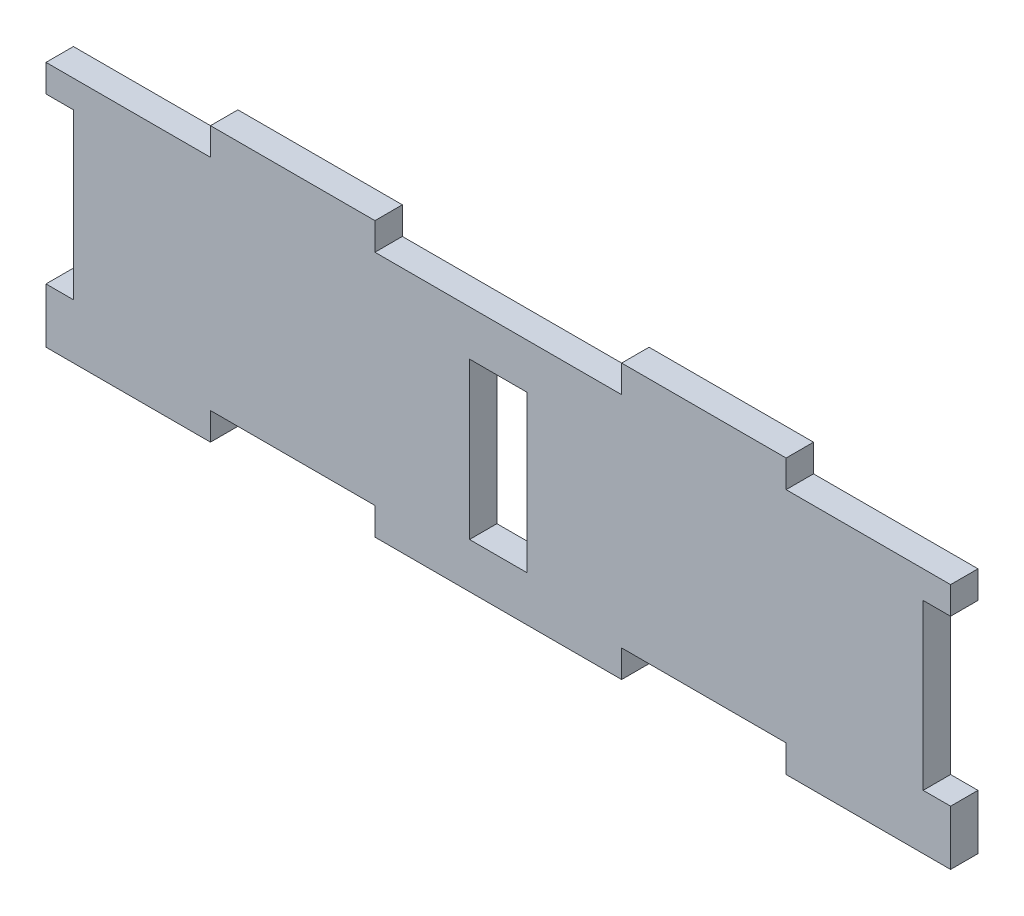
SolidWorks part; units mm, degrees
ref_plane "Front Plane" through (0, 0, 0) normal (0, 0, 1) x (1, 0, 0)
ref_plane "Top Plane" through (0, 0, 0) normal (0, 1, 0) x (1, 0, 0)
ref_plane "Right Plane" through (0, 0, 0) normal (1, 0, 0) x (0, 0, -1)
sketch "Sketch2" plane through (0, 0, 0) normal (0, 0, 1) x (1, 0, 0)
  line L0 (144.257, 80.7785) -> (144.257, 85.7785)
  line L1 (-20.743, 40.7785) -> (9.257, 40.7785)
  line L2 (-20.743, 40.7785) -> (-20.743, 50.7785)
  line L3 (-20.743, 85.7785) -> (9.257, 85.7785)
  line L4 (144.257, 40.7785) -> (144.257, 50.7785)
  line L5 (-20.743, 80.7785) -> (-20.743, 85.7785)
  line L6 (39.257, 40.7785) -> (84.257, 40.7785)
  line L7 (114.257, 40.7785) -> (144.257, 40.7785)
  line L8 (9.257, 40.7785) -> (9.257, 45.7785)
  line L9 (144.257, 50.7785) -> (139.257, 50.7785)
  line L10 (9.257, 45.7785) -> (39.257, 45.7785)
  line L11 (144.257, 80.7785) -> (139.257, 80.7785)
  line L12 (139.257, 50.7785) -> (139.257, 80.7785)
  line L13 (-20.743, 50.7785) -> (-15.743, 50.7785)
  line L14 (39.257, 40.7785) -> (39.257, 45.7785)
  line L15 (-20.743, 80.7785) -> (-15.743, 80.7785)
  line L16 (-15.743, 50.7785) -> (-15.743, 80.7785)
  line L17 (39.257, 85.7785) -> (84.257, 85.7785)
  line L18 (84.257, 40.7785) -> (84.257, 45.7785)
  line L19 (84.257, 45.7785) -> (114.257, 45.7785)
  line L20 (114.257, 40.7785) -> (114.257, 45.7785)
  line L21 (114.257, 85.7785) -> (144.257, 85.7785)
  line L22 (9.257, 85.7785) -> (9.257, 90.7785)
  line L23 (9.257, 90.7785) -> (39.257, 90.7785)
  line L24 (39.257, 85.7785) -> (39.257, 90.7785)
  line L26 (84.257, 85.7785) -> (84.257, 90.7785)
  line L27 (84.257, 90.7785) -> (114.257, 90.7785)
  line L28 (114.257, 85.7785) -> (114.257, 90.7785)
  line L29 (67.007, 77.5285) -> (56.507, 77.5285)
  line L30 (67.007, 77.5285) -> (67.007, 49.0285)
  line L31 (67.007, 49.0285) -> (56.507, 49.0285)
  line L32 (56.507, 77.5285) -> (56.507, 49.0285)
  dimension "D1" = 30
  dimension "D2" = 45
  dimension "D3" = 5
  dimension "D4" = 5
  dimension "D5" = 5
  dimension "D6" = 30
  dimension "D7" = 30
  dimension "D8" = 30
  dimension "D9" = 5
  dimension "D10" = 5
  dimension "D11" = 5
  dimension "D12" = 5
  dimension "D13" = 165
  dimension "D14" = 5
  dimension "D15" = 30
  dimension "D16" = 30
  dimension "D17" = 30
  dimension "D18" = 30
  dimension "D19" = 30
  dimension "D20" = 28.5
  dimension "D21" = 10.5
  dimension "D22" = 8.25
  dimension "D23" = 72.25
extrude "Boss-Extrude2" add sketch "Sketch2" along normal blind 5
